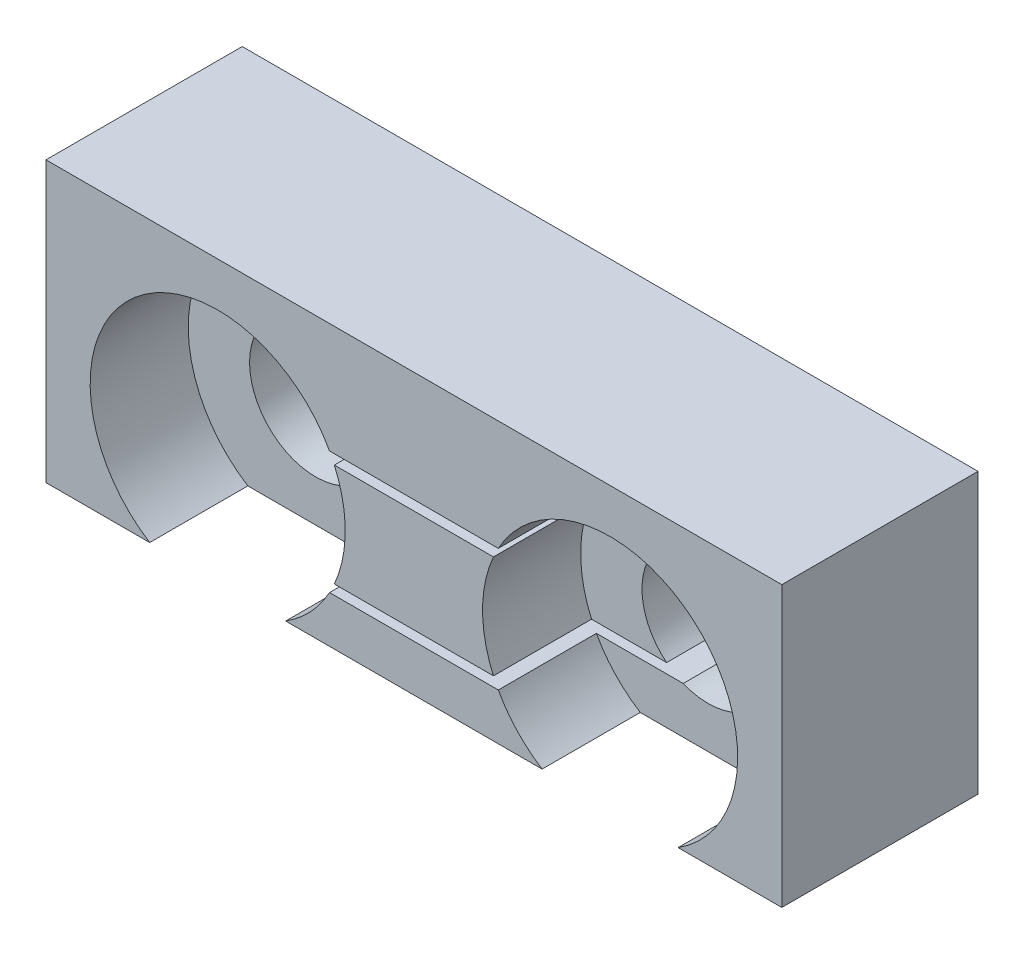
SolidWorks part; units mm, degrees
ref_plane "Front Plane" through (0, 0, 0) normal (0, 0, 1) x (1, 0, 0)
ref_plane "Top Plane" through (0, 0, 0) normal (0, 1, 0) x (1, 0, 0)
ref_plane "Right Plane" through (0, 0, 0) normal (1, 0, 0) x (0, 0, -1)
sketch "Sketch1" plane through (0, 0, 0) normal (0, 0, 1) x (1, 0, 0)
  line L1 (-75, -35) -> (75, -35)
  line L2 (-75, -35) -> (-75, 35)
  line L3 (-75, 35) -> (75, 35)
  line L4 (75, -35) -> (75, 35)
  line L5 (-75, -35) -> (75, 35) construction
  line L6 (-75, 35) -> (75, -35) construction
  point P0 (0, 0)
  dimension "D1" = 150
  dimension "D2" = 70
extrude "Boss-Extrude1" add sketch "Sketch1" along normal blind 40
sketch "Sketch2" plane through (0, 0, 40) normal (0, 0, 1) x (1, 0, 0)
  line L0 (0, 0) -> (0, 50000) construction
  circle A0 centre (40, 0) radius 2.75
  circle A1 centre (-40, 0) radius 2.75
  point P2 (0, 0)
  dimension "D1" = 5.5
  dimension "D2" = 40
extrude "ShaftFits" cut sketch "Sketch2" against normal up to next
sketch "Sketch3" plane through (0, 0, 40) normal (0, 0, 1) x (1, 0, 0)
  line L0 (0, 0) -> (0, 50000) construction
  circle A0 centre (40, 0) radius 12.5
  circle A1 centre (-40, 0) radius 12.5
  dimension "D1" = 25
extrude "Pulley" cut sketch "Sketch3" against normal blind 30
sketch "Sketch4" plane through (0, 0, 40) normal (0, 0, 1) x (1, 0, 0)
  line L0 (0, 0) -> (0, 50000) construction
  circle A0 centre (40, 0) radius 25
  circle A1 centre (-40, 0) radius 25
  dimension "D1" = 50
extrude "Gears fits" cut sketch "Sketch4" against normal blind 20
sketch "Sketch5" plane through (0, 0, 40) normal (0, 0, 1) x (1, 0, 0)
  line L0 (75, -35) -> (75, 35) construction
  line L1 (-75, -35) -> (75, -35)
  line L2 (-75, -35) -> (-75, -22)
  line L3 (-75, -22) -> (75, -22)
  line L4 (75, -35) -> (75, -22)
  circle A0 centre (40, 0) radius 25 construction
  dimension "D1" = 22
extrude "Gear letout" cut sketch "Sketch5" against normal up to next
sketch "Sketch8" plane through (0, 0, 40) normal (0, 0, 1) x (1, 0, 0)
  line L0 (0, 0) -> (-50000, 0) construction
  line L1 (-40, 10.5) -> (40, 10.5)
  line L2 (-40, 10.5) -> (-40, 12.5)
  line L3 (-40, 12.5) -> (40, 12.5)
  line L4 (40, 10.5) -> (40, 12.5)
  line L5 (40, -10.5) -> (40, -12.5)
  line L6 (-40, -12.5) -> (40, -12.5)
  line L7 (-40, -10.5) -> (-40, -12.5)
  line L8 (-40, -10.5) -> (40, -10.5)
  circle A0 centre (-40, 0) radius 12.5 construction
  point P9 (-40, 0)
  point P10 (40, 0)
  dimension "D1" = 2
extrude "Closed-loop timing belt" cut sketch "Sketch8" against normal up to surface (30 mm away) up to face at (-52.5, 0, 10)
sketch "Sketch6" plane through (0, 0, 40) normal (0, 0, 1) x (1, 0, 0)
  line L0 (0, 0) -> (0, 50000) construction
  circle A0 centre (40, 0) radius 26
  arc A1 (51.8743, -22) -> (18.3494, 12.5) centre (40, 0) ccw construction
  circle A2 centre (-40, 0) radius 26
  dimension "D1" = 1
extrude "Gear margin" cut sketch "Sketch6" against normal up to surface (20 mm away) up to face at (-38.5593, -3.7511, 20)
sketch "Sketch7" plane through (0, 0, 20) normal (0, 0, 1) x (1, 0, 0)
  line L0 (0, 0) -> (0, 50000) construction
  circle A0 centre (40, 0) radius 13.5
  circle A1 centre (40, 0) radius 12.5 construction
  circle A2 centre (-40, 0) radius 13.5
  dimension "D1" = 1
extrude "Pulley margin" cut sketch "Sketch7" against normal up to surface (10 mm away) up to face at (0, 0, 10)
